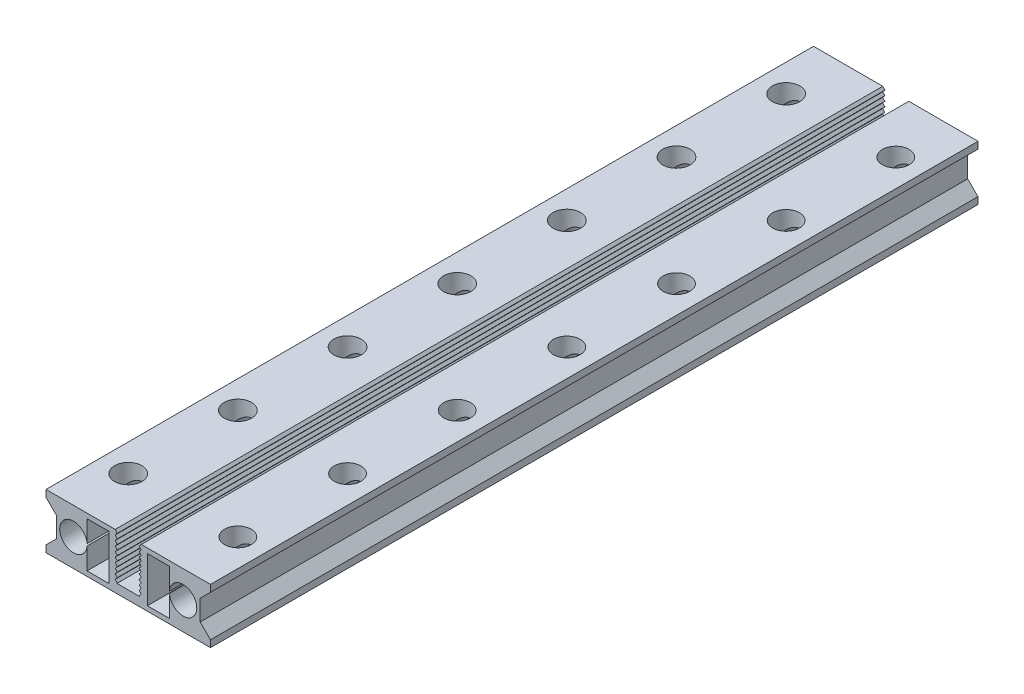
SolidWorks part; units mm, degrees
ref_plane "前视基准面" through (0, 0, 0) normal (0, 0, 1) x (1, 0, 0)
ref_plane "上视基准面" through (0, 0, 0) normal (0, 1, 0) x (1, 0, 0)
ref_plane "右视基准面" through (0, 0, 0) normal (1, 0, 0) x (0, 0, -1)
sketch "草图1" plane through (0, 0, 0) normal (0, 0, 1) x (1, 0, 0)
  line L0 (-12, 8) -> (-12, 7)
  line L1 (-12, 7) -> (-10.5, 5.5)
  line L2 (-10.5, 5.5) -> (-10.5, 2.5)
  line L3 (-10.5, 2.5) -> (-12, 1)
  line L4 (-12, 1) -> (-12, 0)
  line L5 (-12, 0) -> (12, 0)
  line L6 (12, 0) -> (12, 1)
  line L7 (12, 1) -> (10.5, 2.5)
  line L8 (10.5, 2.5) -> (10.5, 5.5)
  line L9 (10.5, 5.5) -> (12, 7)
  line L10 (12, 7) -> (12, 8)
  line L11 (12, 8) -> (1.9, 8)
  line L12 (0, 0) -> (0, 8) construction
  line L13 (-8, 4) -> (8, 4) construction
  line L14 (-1.9, 8) -> (-1.9, 1.3)
  line L15 (-6.005, 7.3) -> (-2.8, 7.3)
  line L16 (-6.005, 7.3) -> (-6.005, 4.1413)
  line L17 (-6.005, 0.7) -> (-2.8, 0.7)
  line L18 (-2.8, 7.3) -> (-2.8, 0.7)
  line L19 (-1.9, 1.3) -> (1.9, 1.3)
  line L20 (1.9, 1.3) -> (1.9, 8)
  line L21 (-1.9, 8) -> (-12, 8)
  line L22 (-6.005, 3.8587) -> (-6.005, 0.7)
  line L23 (2.8, 7.3) -> (6.005, 7.3)
  line L24 (2.8, 7.3) -> (2.8, 0.7)
  line L25 (2.8, 0.7) -> (6.005, 0.7)
  line L26 (6.005, 7.3) -> (6.005, 4.1413)
  line L27 (6.005, 3.8587) -> (6.005, 0.7)
  arc A0 (-6.005, 4.1413) -> (-6, 4) centre (-8, 4) ccw
  arc A1 (6.005, 3.8587) -> (6.005, 4.1413) centre (8, 4) ccw
  point P19 (10.5, 4)
  point P24 (-2.8, 4)
  point P27 (0, 1.3)
  dimension "D4" = 4
  dimension "D1" = 24
  dimension "D2" = 8
  dimension "D3" = 45
  dimension "D5" = 16
  dimension "D6" = 8
  dimension "D7" = 3
  dimension "D8" = 1
  dimension "D9" = 4
  dimension "D10" = 3.8
  dimension "D11" = 1.3
  dimension "D12" = 5.6
  dimension "D13" = 2.8
  dimension "D14" = 12.01
  dimension "D15" = 0.7
extrude "凸台-拉伸2" add sketch "草图1" along normal blind 112 contours L14 L21 L0 L1 L2 L3 L4 L5 L6 L7 L8 L9 L10 L11 L20 L19 A1 L27 L25 L24 L23 L26 A0 L16 L15 L18 L17 L22
sketch "草图3" plane through (0, 0, 112) normal (0, 0, 1) x (1, 0, 0)
  line L0 (-1.9, 8) -> (-1.6, 7.65)
  line L1 (-1.6, 7.65) -> (-1.9, 7.3)
  line L2 (-1.9, 8) -> (-1.9, 1.3) construction
  line L3 (-1.9, 7.3) -> (-1.9, 8)
  point P7 (-1.9, 7.65)
  dimension "D1" = 0.7
  dimension "D2" = 0.3
extrude "凸台-拉伸3" add sketch "草图3" against normal up to surface (112 mm away) up to face at (5.6025, 4, 0)
pattern_linear "阵列(线性)1" count 10 spacing 0.7 along (0, -1, 0) of "凸台-拉伸3"
mirror "镜向1" about plane through (0, 0, 0) normal (1, 0, 0) of "阵列(线性)1", "凸台-拉伸3"
sketch "草图4" plane through (0, 8, 0) normal (0, 1, 0) x (1, 0, 0)
  line L1 (12, 0) -> (1.9, 0) construction
  circle A0 centre (-8, -8) radius 2
  circle A1 centre (8, -8) radius 1.95
  dimension "D1" = 16
  dimension "D4" = 3.9
  dimension "D5" = 4
  dimension "D2" = 8
  dimension "D3" = 8
extrude "切除-拉伸1" cut sketch "草图4" against normal through all
pattern_linear "阵列(线性)2" count 7 spacing 16 along (0, 0, 1) of "切除-拉伸1"
equation "\"D13@草图1\"=\"D12@草图1\"/2"
